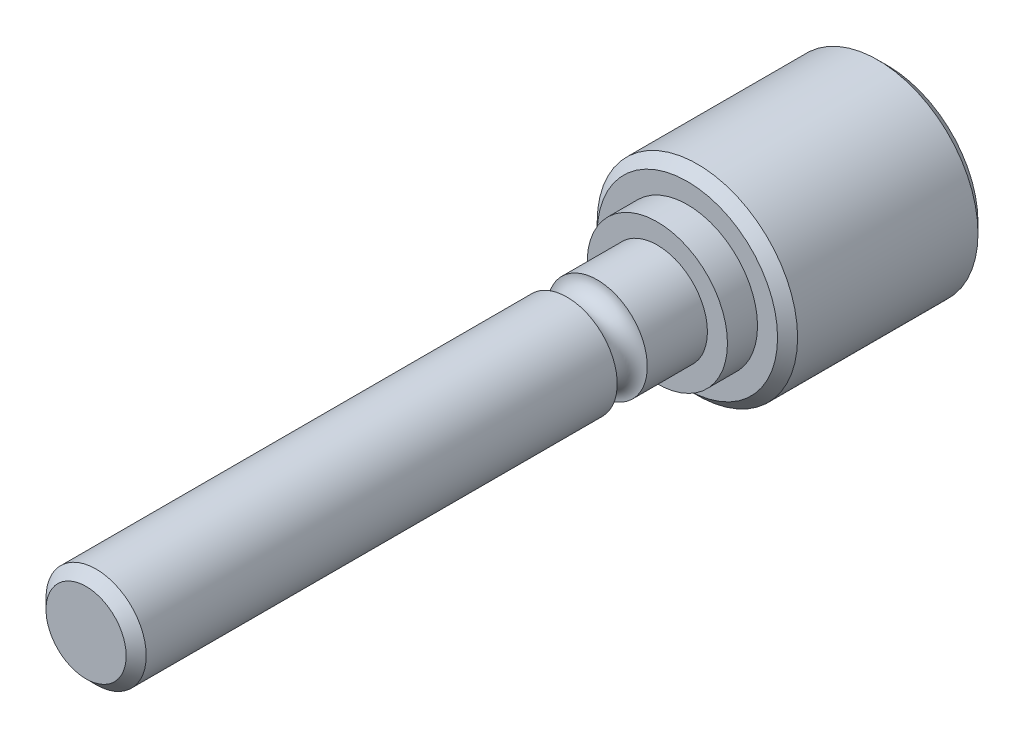
SolidWorks part; units mm, degrees
material "Liga de aço"
ref_plane "Plano frontal" through (0, 0, 0) normal (0, 0, 1) x (1, 0, 0)
ref_plane "Plano superior" through (0, 0, 0) normal (0, 1, 0) x (1, 0, 0)
ref_plane "Plano direito" through (0, 0, 0) normal (1, 0, 0) x (0, 0, -1)
sketch "Esboço1" plane through (0, 0, 0) normal (0, 0, 1) x (1, 0, 0)
  circle A0 centre (0, 0) radius 10
  dimension "D1" = 20
extrude "Ressalto-extrusão1" add sketch "Esboço1" along normal blind 20
sketch "Esboço2" plane through (0, 0, 20) normal (0, 0, 1) x (1, 0, 0)
  circle A0 centre (0, 0) radius 7
  dimension "D1" = 14
extrude "Ressalto-extrusão2" add sketch "Esboço2" along normal blind 3
sketch "Esboço3" plane through (0, 0, 23) normal (0, 0, 1) x (1, 0, 0)
  circle A0 centre (0, 0) radius 5
  dimension "D1" = 10
extrude "Ressalto-extrusão3" add sketch "Esboço3" along normal blind 57
chamfer "Chanfro1" distance 1 angle 45 1 edges at (10, 0, 0)
chamfer "Chanfro2" distance 1 angle 45 1 edges at (10, 0, 20)
chamfer "Chanfro3" distance 1 angle 45 1 edges at (5, 0, 80)
sketch "Esboço5" plane through (0, 0, 0) normal (0, 1, 0) x (1, 0, 0)
  line L0 (-5, -23) -> (5, -23) construction
  circle A0 centre (-5, -30.5) radius 1.5
  dimension "D1" = 3
  dimension "D2" = 7.5
  dimension "D3" = 5
ref_plane "Plano de Referência" through (0, 0, 30.5) normal (0, 0, 1) x (1, 0, 0)
sketch "Esboço7" plane through (0, 0, 30.5) normal (0, 0, 1) x (1, 0, 0)
  circle A0 centre (0, 0) radius 5
  dimension "D1" = 10
sweep "Varredura de corte1" cut profiles "Esboço5" path "Esboço7"
